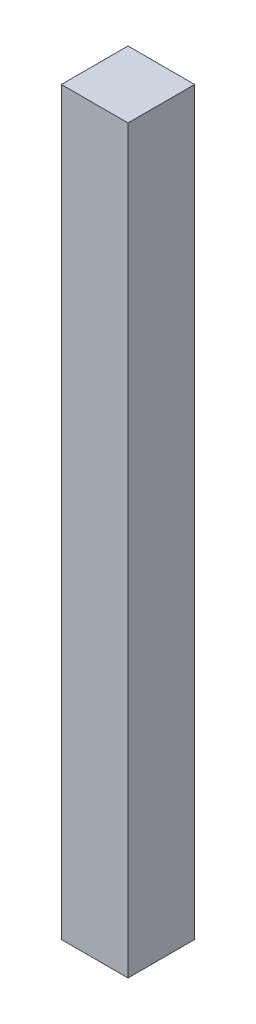
SolidWorks part; units mm, degrees
ref_plane "Front Plane" through (0, 0, 0) normal (0, 0, 1) x (1, 0, 0)
ref_plane "Top Plane" through (0, 0, 0) normal (0, 1, 0) x (1, 0, 0)
ref_plane "Right Plane" through (0, 0, 0) normal (1, 0, 0) x (0, 0, -1)
other "Configuration Table"
sketch "Sketch1" plane through (0, 0, 0) normal (0, 0, 1) x (1, 0, 0)
  line L1 (637, 1590) -> (655, 1590)
  line L2 (637, 1590) -> (637, 1790)
  line L3 (637, 1790) -> (655, 1790)
  line L4 (655, 1590) -> (655, 1790)
extrude "TOPPING_klape_kat1_gazli_amortisor_2_1" add sketch "Sketch1" along normal blind 18 from offset 8 separate body
